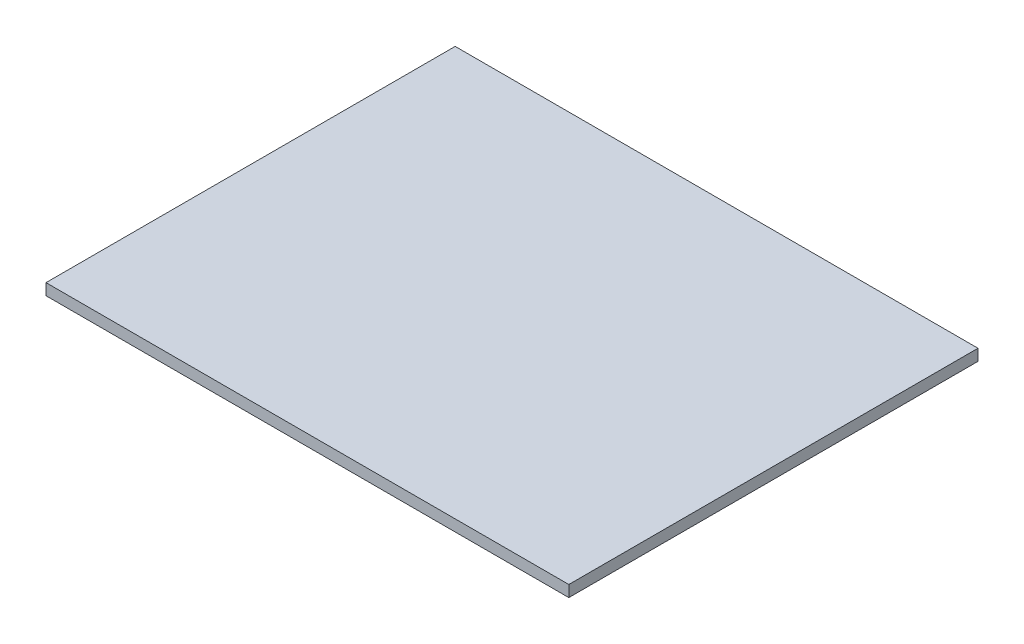
SolidWorks part; units mm, degrees
ref_plane "Front Plane" through (0, 0, 0) normal (0, 0, 1) x (1, 0, 0)
ref_plane "Top Plane" through (0, 0, 0) normal (0, 1, 0) x (1, 0, 0)
ref_plane "Right Plane" through (0, 0, 0) normal (1, 0, 0) x (0, 0, -1)
sketch "Sketch1" plane through (0, 0, 0) normal (0, 1, 0) x (1, 0, 0)
  line L1 (-292.1, -457.2) -> (292.1, -457.2)
  line L2 (-292.1, -457.2) -> (-292.1, 0)
  line L3 (-292.1, 0) -> (292.1, 0)
  line L4 (292.1, -457.2) -> (292.1, 0)
  line L5 (-292.1, -457.2) -> (292.1, 0) construction
  line L6 (-292.1, 0) -> (292.1, -457.2) construction
  line L7 (292.1, -457.2) -> (304.8, -457.2) construction
  line L8 (292.1, -457.2) -> (292.1, 0) construction
  point P0 (0, -228.6)
extrude "Boss-Extrude1" add sketch "Sketch1" along normal blind 12.7
